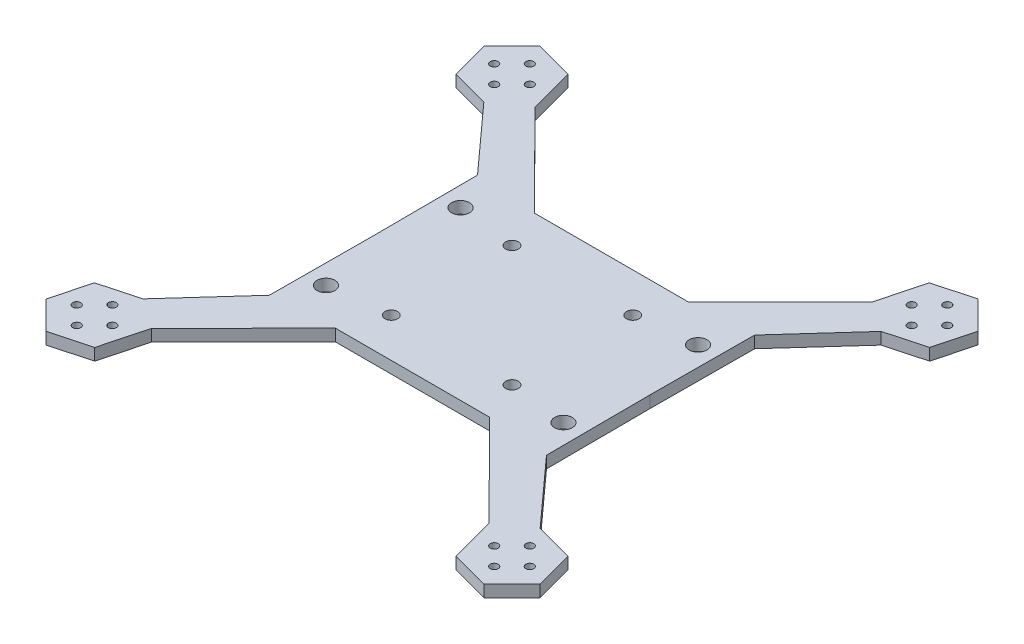
SolidWorks part; units mm, degrees
ref_plane "Front Plane" through (0, 0, 0) normal (0, 0, 1) x (1, 0, 0)
ref_plane "Top Plane" through (0, 0, 0) normal (0, 1, 0) x (1, 0, 0)
ref_plane "Right Plane" through (0, 0, 0) normal (1, 0, 0) x (0, 0, -1)
sketch "Sketch1" plane through (0, 0, 0) normal (0, 1, 0) x (1, 0, 0)
  line L5 (-35, -35) -> (42.6186, 42.6186) construction
  line L6 (-35, 35) -> (35, -35) construction
  line L9 (0, 0) -> (42.4264, 42.4264) construction
  line L10 (52.7307, 48.2307) -> (52.7307, 57.2307) construction
  line L11 (30, 17) -> (30, 0) construction
  line L12 (0, 0) -> (0, 23.6863) construction
  line L28 (0, 0) -> (-174.2372, 0) construction
  line L41 (31.9599, 25.1581) -> (-25.1581, 25.1581) construction
  line L70 (42.6186, 48.4021) -> (19.4638, 25.1581)
  line L72 (48.2307, 52.7307) -> (57.2307, 52.7307) construction
  line L74 (48.2307, 52.7307) -> (52.7307, 48.2307) construction
  line L75 (55.3003, 62.3949) -> (45.646, 59.7881)
  line L77 (45.646, 59.7881) -> (42.6186, 48.4021)
  line L80 (50.185, 43.0729) -> (59.8153, 45.6732)
  line L83 (59.8153, 45.6732) -> (62.3849, 55.3374)
  line L85 (62.3849, 55.3374) -> (55.3003, 62.3949)
  line L87 (50.185, 43.0729) -> (35, 26.2883)
  line L88 (35, 26.2883) -> (34.873, 0)
  line L89 (34.873, -11.873) -> (34.873, 11.873) construction
  line L90 (-21.8355, 25.1581) -> (21.8355, 25.1581)
  line L94 (35, -26.2883) -> (34.873, 0)
  line L100 (48.2307, -52.7307) -> (52.7307, -48.2307) construction
  line L101 (48.2307, -52.7307) -> (57.2307, -52.7307) construction
  line L102 (52.7307, -48.2307) -> (52.7307, -57.2307) construction
  line L106 (62.3849, -55.3374) -> (55.3003, -62.3949)
  line L111 (59.8153, -45.6732) -> (62.3849, -55.3374)
  line L115 (50.185, -43.0729) -> (59.8153, -45.6732)
  line L116 (45.646, -59.7881) -> (42.6186, -48.4021)
  line L119 (55.3003, -62.3949) -> (45.646, -59.7881)
  line L127 (50.185, -43.0729) -> (35, -26.2883)
  line L128 (35, 26.2883) -> (34.873, 0)
  line L129 (35, -26.2883) -> (34.873, 0)
  line L135 (42.6186, -48.4021) -> (19.4638, -25.1581)
  line L138 (40.4517, 52.7386) -> (49.1512, 44.0725) [skipped]
  line L139 (-21.8355, -25.1581) -> (21.8355, -25.1581)
  line L140 (-48.2307, 52.7307) -> (-52.7307, 48.2307) construction
  line L141 (-48.2307, 52.7307) -> (-57.2307, 52.7307) construction
  line L142 (-52.7307, 48.2307) -> (-52.7307, 57.2307) construction
  line L143 (-62.3849, 55.3374) -> (-55.3003, 62.3949)
  line L144 (-59.8153, 45.6732) -> (-62.3849, 55.3374)
  line L145 (-50.185, 43.0729) -> (-59.8153, 45.6732)
  line L146 (-45.646, 59.7881) -> (-42.6186, 48.4021)
  line L147 (-55.3003, 62.3949) -> (-45.646, 59.7881)
  line L148 (-50.185, 43.0729) -> (-35, 26.2883)
  line L149 (-42.6186, 48.4021) -> (-19.4638, 25.1581)
  line L150 (-35, 26.2883) -> (-34.873, 0)
  line L151 (-35, -26.2883) -> (-34.873, 0)
  line L152 (-50.185, -43.0729) -> (-35, -26.2883)
  line L153 (-42.6186, -48.4021) -> (-19.4638, -25.1581)
  line L154 (-52.7307, -48.2307) -> (-52.7307, -57.2307) construction
  line L155 (-48.2307, -52.7307) -> (-57.2307, -52.7307) construction
  line L156 (-48.2307, -52.7307) -> (-52.7307, -48.2307) construction
  line L157 (-55.3003, -62.3949) -> (-45.646, -59.7881)
  line L158 (-45.646, -59.7881) -> (-42.6186, -48.4021)
  line L159 (-50.185, -43.0729) -> (-59.8153, -45.6732)
  line L160 (-59.8153, -45.6732) -> (-62.3849, -55.3374)
  line L161 (-62.3849, -55.3374) -> (-55.3003, -62.3949)
  circle A0 centre (-15.25, 15.25) radius 1.6
  circle A1 centre (15.25, 15.25) radius 1.6
  circle A2 centre (15.25, -15.25) radius 1.6
  circle A3 centre (-15.25, -15.25) radius 1.6
  circle A18 centre (30, 17) radius 2.25
  circle A19 centre (30, -17) radius 2.25
  circle A20 centre (-30, -17) radius 2.25
  circle A21 centre (-30, 17) radius 2.25
  circle A69 centre (52.7307, 52.7307) radius 8.6603 construction
  circle A70 centre (52.7307, 57.2307) radius 1
  circle A71 centre (52.7307, 48.2307) radius 1
  circle A72 centre (48.2307, 52.7307) radius 1
  circle A73 centre (57.2307, 52.7307) radius 1
  circle A124 centre (52.7307, -52.7307) radius 8.6603 construction
  circle A125 centre (57.2307, -52.7307) radius 1
  circle A126 centre (48.2307, -52.7307) radius 1
  circle A127 centre (52.7307, -48.2307) radius 1
  circle A128 centre (52.7307, -57.2307) radius 1
  circle A129 centre (-52.7307, 52.7307) radius 8.6603 construction
  circle A130 centre (-57.2307, 52.7307) radius 1
  circle A131 centre (-48.2307, 52.7307) radius 1
  circle A132 centre (-52.7307, 48.2307) radius 1
  circle A133 centre (-52.7307, 57.2307) radius 1
  circle A134 centre (-52.7307, -52.7307) radius 8.6603 construction
  circle A135 centre (-52.7307, -57.2307) radius 1
  circle A136 centre (-52.7307, -48.2307) radius 1
  circle A137 centre (-48.2307, -52.7307) radius 1
  circle A138 centre (-57.2307, -52.7307) radius 1
  point P0 (0, 0)
  point P8 (52.7307, 52.7307)
  point P9 (52.7307, 52.7307)
  point P17 (0, 0)
  point P45 (24.8566, 0)
  point P47 (30, 0)
  point P90 (0, 25.1581)
  point P95 (0, -25.1581)
  point P96 (0, 25.1581)
  point P99 (0, 25.1581)
  point P110 (0, -25.1581)
  point P118 (0, 0)
  point P126 (0, -25.1581)
  dimension "D3" = 3.2
  dimension "D16" = 4.5
  dimension "D1" = 70
  dimension "D2" = 4.5
  dimension "D4" = 30.5
  dimension "D6" = 4.5
  dimension "D7" = 20
  dimension "D15" = 17
  dimension "D12" = 30
  dimension "D5" = 4
  dimension "D17" = 2
extrude "Boss-Extrude1" add sketch "Sketch1" along normal blind 3
sketch "Sketch4" plane through (0, 0, 0) normal (0, -1, 0) x (1, 0, 0)
  circle A0 centre (0, 0) radius 4.9
  circle A1 centre (0, 0) radius 6.495
  dimension "D1" = 9.8
extrude "Boss-Extrude3" add sketch "Sketch4" along normal blind 5
sketch "Sketch6" plane through (0, 0, 35) normal (0, 0, 1) x (1, 0, 0)
  line L0 (-6.495, 0) -> (6.495, 0) construction
  line L1 (-4.2416, -1.8916) -> (4.2416, -1.8916)
  line L2 (-4.2416, -1.8916) -> (-4.2416, 0)
  line L3 (-4.2416, 0) -> (4.2416, 0)
  line L4 (4.2416, -1.8916) -> (4.2416, 0)
  line L5 (-4.2416, -1.8916) -> (4.2416, 0) construction
  line L6 (-4.2416, 0) -> (4.2416, -1.8916) construction
  point P0 (0, -0.9458)
extrude "Cut-Extrude3" cut sketch "Sketch6" against normal blind 34
